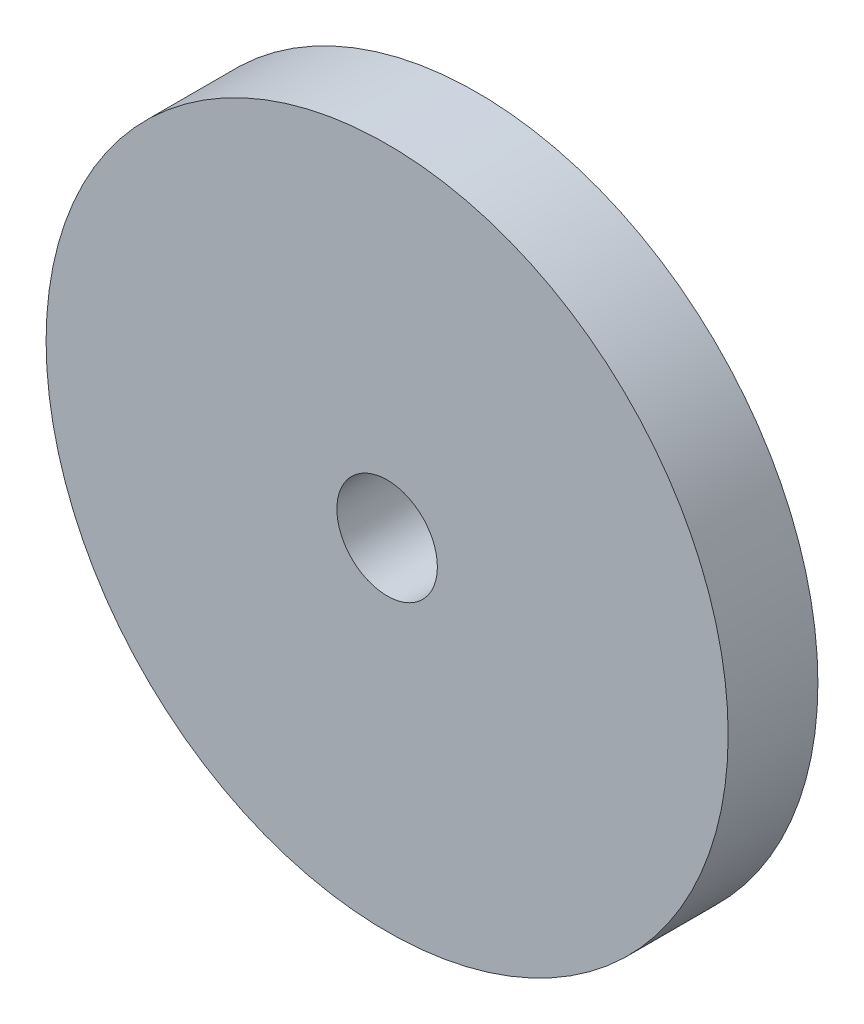
SolidWorks part; units mm, degrees
ref_plane "Piano frontale" through (0, 0, 0) normal (0, 0, 1) x (1, 0, 0)
ref_plane "Piano superiore" through (0, 0, 0) normal (0, 1, 0) x (1, 0, 0)
ref_plane "Piano destro" through (0, 0, 0) normal (1, 0, 0) x (0, 0, -1)
sketch "Sketch1" plane through (0, 0, 0) normal (0, 0, 1) x (1, 0, 0)
  line L1 (150, 0) -> (150, 150) construction
  circle A0 centre (0, 0) radius 19
  circle A1 centre (0, 0) radius 2.8
  point P5 (0, -10)
  point P7 (150, -10)
  point P8 (0, 10)
  point P9 (150, 10)
  dimension "D1" = 38
  dimension "D2" = 5.6
  dimension "D4" = 150
extrude "Boss-Extrude1" add sketch "Sketch1" along normal mid plane 5
